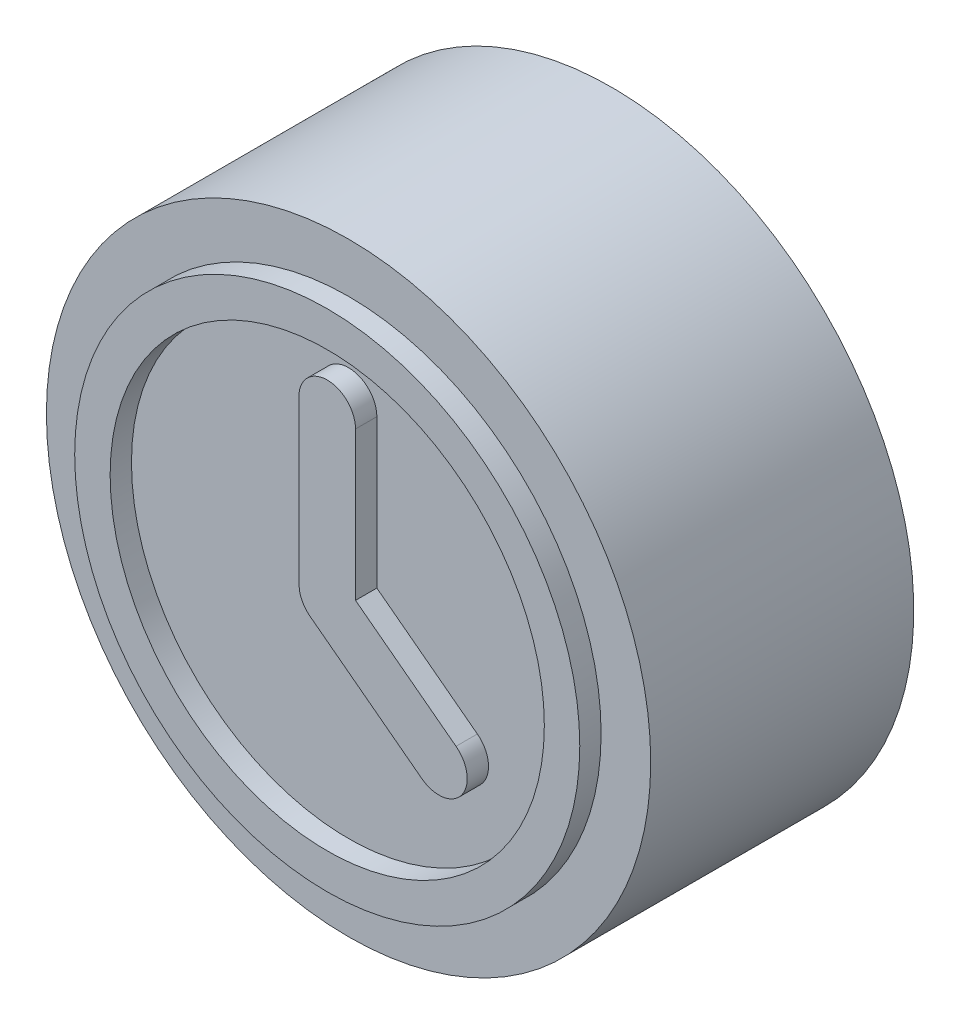
SolidWorks part; units mm, degrees
ref_plane "Front Plane" through (0, 0, 0) normal (0, 0, 1) x (1, 0, 0)
ref_plane "Top Plane" through (0, 0, 0) normal (0, 1, 0) x (1, 0, 0)
ref_plane "Right Plane" through (0, 0, 0) normal (1, 0, 0) x (0, 0, -1)
sketch "Sketch1" plane through (0, 0, 0) normal (0, 0, 1) x (1, 0, 0)
  circle A0 centre (0, 0) radius 8.5
  dimension "D1" = 17
extrude "Boss-Extrude1" add sketch "Sketch1" along normal blind 4.4
sketch "Sketch2" plane through (0, 0, 4.4) normal (0, 0, 1) x (1, 0, 0)
  line L11 (0, 0) -> (0, 4.571) construction
  line L12 (-0.7958, 0) -> (-0.7958, 4.571)
  line L13 (0.7958, 0.3955) -> (0.7958, 4.571)
  line L14 (0, 0) -> (3.1421, -2.3802) construction
  line L15 (0.7958, 0.3955) -> (3.6226, -1.7459)
  line L16 (-0.4805, -0.6343) -> (2.6616, -3.0145)
  line L17 (0.2705, -1.2032) -> (-1.2315, -0.0654) construction
  circle A0 centre (0, 0) radius 7.1043
  circle A1 centre (0, 0) radius 6.1073
  arc A2 (-0.7958, 0) -> (-0.4805, -0.6343) centre (0, 0) ccw construction
  arc A3 (0.7958, 4.571) -> (-0.7958, 4.571) centre (0, 4.571) ccw
  arc A4 (-0.7958, 0) -> (-0.4805, -0.6343) centre (0, 0) ccw construction
  arc A5 (2.6616, -3.0145) -> (3.6226, -1.7459) centre (3.1421, -2.3802) ccw
  circle A6 centre (0, 0) radius 8.5 construction
  spline S0 degree 3 poles (-0.7958, 0) (-0.7829, -0.1804) (-0.7683, -0.2256) (-0.6772, -0.4376) (-0.5735, -0.5638) (-0.4805, -0.6343) knots 0 0 0 0 0.52842 0.62842 1 1 1 1
  point P4 (0, 2.2855)
  point P10 (1.5711, -1.1901)
  point P18 (-0.7126, -0.3542)
  dimension "D1" = 360
extrude "Boss-Extrude2" add sketch "Sketch2" along normal blind 0.6 contours A0 A1 | L12 S0 L16 A5 L15 L13 A3
sketch "Sketch3" plane through (0, 0, 0) normal (0, 0, -1) x (-1, 0, 0)
  circle A0 centre (0, 0) radius 5.8
  dimension "D1" = 11.6
extrude "Cut-Extrude1" cut sketch "Sketch3" against normal blind 4
sketch "Sketch4" plane through (0, 0, 0) normal (0, 0, -1) x (-1, 0, 0)
  circle A1 centre (0, 0) radius 8.5
  circle A2 centre (0, 0) radius 8.5
  circle A4 centre (0, 0) radius 7.5
  dimension "D2" = 1
  dimension "D1" = 0
extrude "Boss-Extrude3" add sketch "Sketch4" along normal blind 3
sketch "Sketch6" plane through (0, 0, 0) normal (0, 1, 0) x (1, 0, 0)
  line L6 (7.5, 0) -> (5.8, -1.7)
  line L7 (5.8, -1.7) -> (5.8, 0)
  line L8 (5.8, 0) -> (7.5, 0)
  line L9 (7.5, 0) -> (-7.5, 0) construction
  line L10 (5.8, 0) -> (-5.8, 0) construction
  point P2 (0, 0)
  point P6 (0, 0)
  point P9 (0, 0)
  point P11 (0, 0)
  dimension "D1" = 45
ref_axis "Axis1" through (0, 0, -5.5) along (0, 0, 1)
revolve "Cut-Revolve1" cut sketch "Sketch6" angle 360 about axis through (0, 0, -5.5) along (0, 0, 1)
